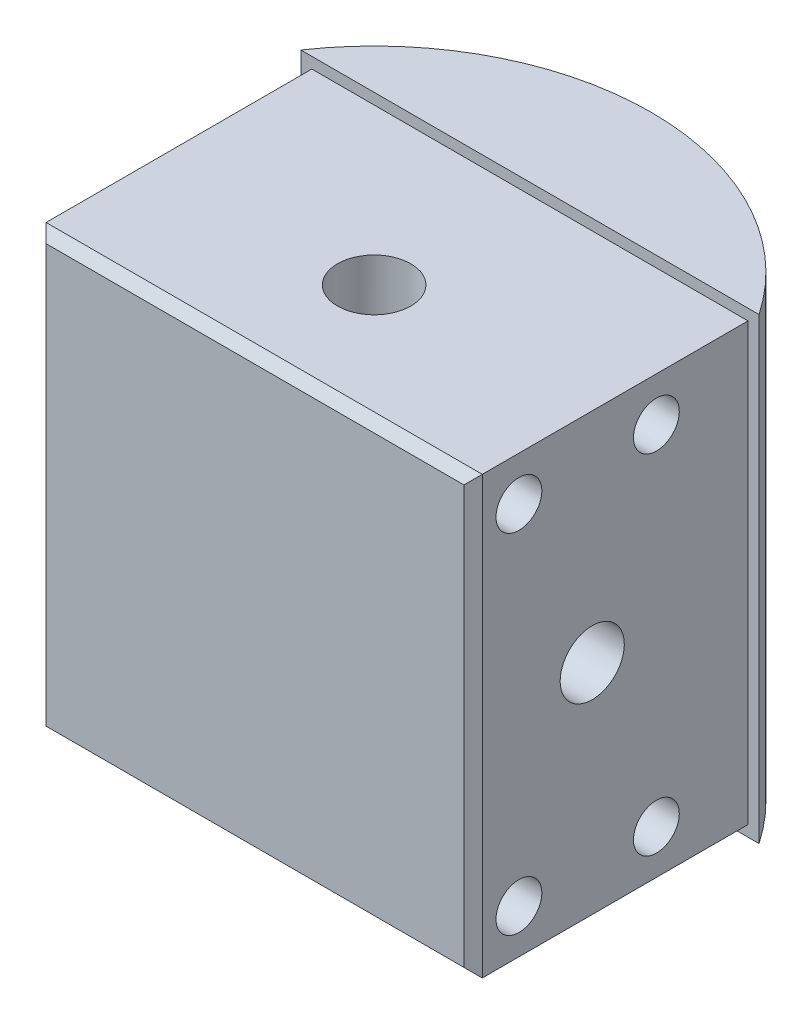
SolidWorks part; units mm, degrees
ref_plane "Alzado" through (0, 0, 0) normal (0, 0, 1) x (1, 0, 0)
ref_plane "Planta" through (0, 0, 0) normal (0, 1, 0) x (1, 0, 0)
ref_plane "Vista lateral" through (0, 0, 0) normal (1, 0, 0) x (0, 0, -1)
sketch "Croquis1" plane through (0, 0, 0) normal (0, 0, 1) x (1, 0, 0)
  line L1 (-23.8, 23.8) -> (23.8, 23.8)
  line L2 (-23.8, 23.8) -> (-23.8, -23.8)
  line L3 (-23.8, -23.8) -> (23.8, -23.8)
  line L4 (23.8, 23.8) -> (23.8, -23.8)
  line L5 (-23.8, 23.8) -> (23.8, -23.8) construction
  line L6 (-23.8, -23.8) -> (23.8, 23.8) construction
  point P0 (0, 0)
  dimension "D1" = 47.6
  dimension "D2" = 47.6
extrude "Saliente-Extruir1" add sketch "Croquis1" along normal blind 30
sketch "Croquis2" plane through (0, 0, 0) normal (0, 1, 0) x (1, 0, 0)
  line L0 (0, 0) -> (0, -17) construction
  line L1 (-25, 0) -> (25, 0)
  arc A0 (-25, 0) -> (25, 0) centre (0, -17) cw
  dimension "D1" = 50
extrude "Saliente-Extruir2" add sketch "Croquis2" along normal blind 25 and the other way blind 25
sketch "Croquis3" plane through (0, 23.8, 0) normal (0, 1, 0) x (1, 0, 0)
  line L0 (23.8, 0) -> (-23.8, 0) construction
  line L1 (0, 0) -> (0, -17) construction
  circle A0 centre (0, -17) radius 4
  point P2 (0, 0)
  dimension "D1" = 8
  dimension "D2" = 17
extrude "Cortar-Extruir1" cut sketch "Croquis3" against normal through all
sketch "Croquis4" plane through (23.8, 0, 0) normal (1, 0, 0) x (0, 0, -1)
  line L0 (-30, 19) -> (0, 19) construction
  line L1 (-30, -23.8) -> (-30, 23.8) construction
  line L2 (0, -25) -> (0, 25) construction
  line L3 (0, 0) -> (-30, 0) construction
  line L5 (-25, 23.8) -> (-25, -23.8) construction
  line L6 (-30, 23.8) -> (0, 23.8) construction
  line L7 (-30, -23.8) -> (0, -23.8) construction
  line L8 (-10, 23.8) -> (-10, -23.8) construction
  line L9 (0, -23.8) -> (0, 23.8) construction
  line L10 (13.2324, 25) -> (0, 25) construction
  circle A0 centre (-10, 19) radius 2.5
  circle A1 centre (-25, 19) radius 2.5
  circle A2 centre (-25, -19) radius 2.5
  circle A3 centre (-10, -19) radius 2.5
  circle A4 centre (-17, 0) radius 3.5
  dimension "D4" = 5
  dimension "D5" = 5
  dimension "D6" = 7
  dimension "D7" = 17
  dimension "D1" = 10
  dimension "D2" = 15
  dimension "D3" = 6
extrude "Cortar-Extruir2" cut sketch "Croquis4" against normal through all
chamfer "Chaflán1" distance 1 angle 45 4 edges at (-23.8, 0, 30) (0, -23.8, 30) (23.8, 0, 30) (0, 23.8, 30)
